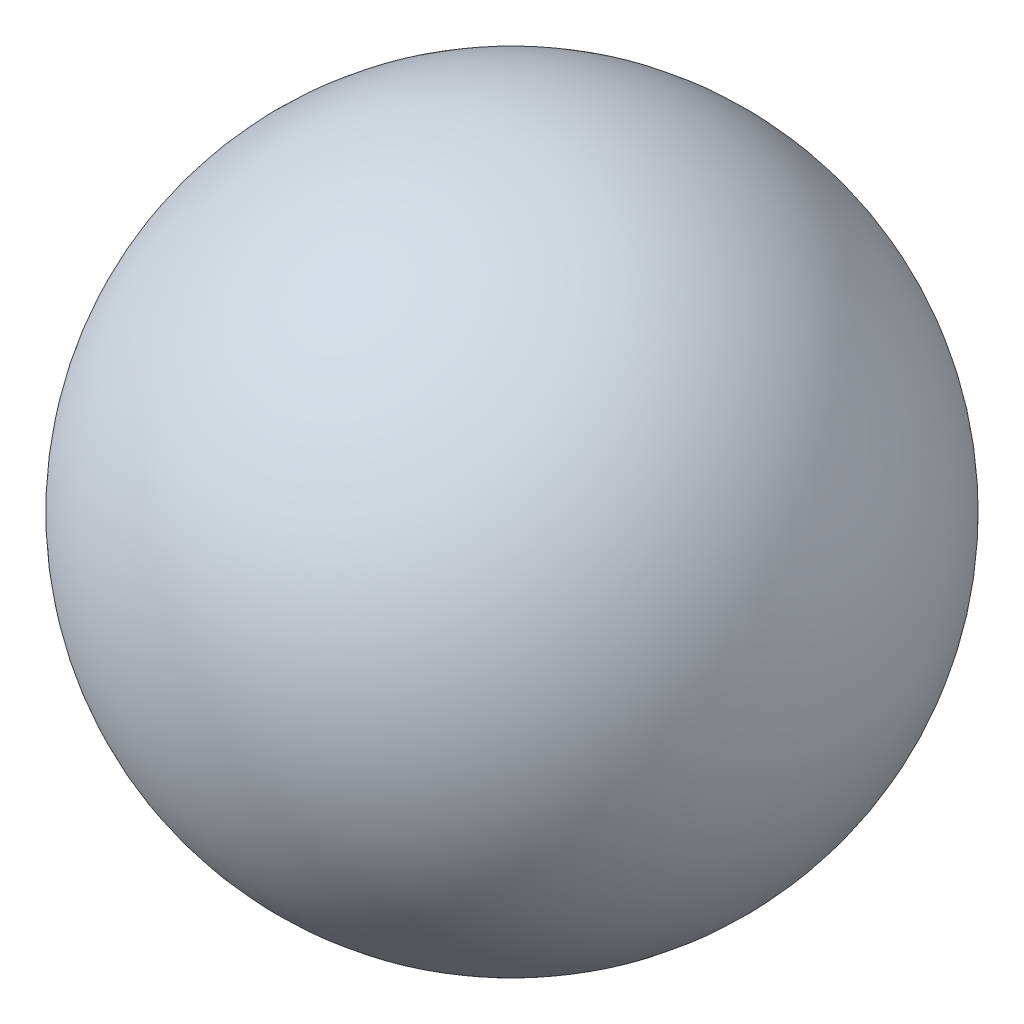
SolidWorks part; units mm, degrees
ref_plane "Front Plane" through (0, 0, 0) normal (1, 0, 0) x (0, 1, 0)
ref_plane "Top Plane" through (0, 0, 0) normal (0, 0, 1) x (0, 1, 0)
ref_plane "Right Plane" through (0, 0, 0) normal (0, 1, 0) x (-1, 0, 0)
sketch "Sketch1" plane through (0, 0, 0) normal (0, 0, 1) x (0, 1, 0)
  line L0 (-76.2, 0) -> (76.2, 0)
  arc A0 (-76.2, 0) -> (76.2, 0) centre (0, 0) cw
  point P4 (0, 0)
  point P5 (0, 0)
  point P6 (0, 0)
  point P7 (0, 0)
  dimension "D1" = 152.4
revolve "Revolve1" add sketch "Sketch1" angle 360 about L0
